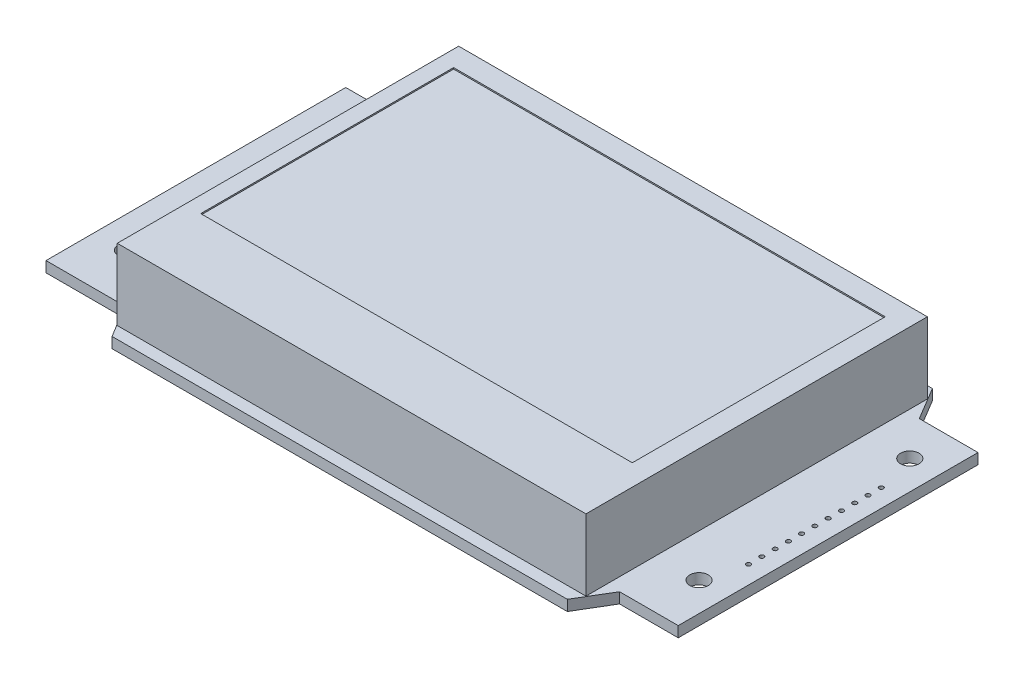
SolidWorks part; units mm, degrees
ref_plane "Front Plane" through (0, 0, 0) normal (0, 0, 1) x (1, 0, 0)
ref_plane "Top Plane" through (0, 0, 0) normal (0, 1, 0) x (1, 0, 0)
ref_plane "Right Plane" through (0, 0, 0) normal (1, 0, 0) x (0, 0, -1)
sketch "Sketch1" plane through (0, 0, 0) normal (0, 1, 0) x (1, 0, 0)
  line L0 (-60.0596, 21.17) -> (-60.0596, -23.9912)
  line L1 (35.1904, 21.17) -> (35.1904, -23.9912)
  line L2 (-45.1752, 26.0849) -> (23.4048, 26.0849)
  line L3 (-45.1752, -28.9151) -> (23.4048, -28.9151)
  line L4 (-60.0596, -1.4106) -> (35.1904, -1.4106) construction
  line L5 (-60.0596, -23.9912) -> (-48.2232, -23.9912)
  line L6 (-60.0596, 21.17) -> (-48.2232, 21.17)
  line L7 (35.1904, 21.17) -> (26.3512, 21.17)
  line L8 (35.1904, -23.9912) -> (26.3512, -23.9912)
  line L9 (-10.8852, 26.0849) -> (-10.8852, -28.9151) construction
  line L10 (-48.2232, -23.9912) -> (-45.1752, -28.9151)
  line L11 (26.3512, -23.9912) -> (23.4048, -28.9151)
  line L12 (23.4048, 26.0849) -> (26.3512, 21.17)
  line L13 (-45.1752, 26.0849) -> (-48.2232, 21.17)
  dimension "D1" = 45.1612
  dimension "D2" = 55
  dimension "D3" = 27.4955
  dimension "D4" = 11.8364
  dimension "D5" = 8.8392
  dimension "D6" = 11.7856
  dimension "D7" = 95.25
  dimension "D8" = 68.58
extrude "Boss-Extrude1" add sketch "Sketch1" along normal blind 1.6
sketch "Sketch2" plane through (0, 1.6, 0) normal (0, 1, 0) x (1, 0, 0)
  line L0 (35.1904, -23.9912) -> (35.1904, 21.17) construction
  line L1 (26.3512, -23.9912) -> (35.1904, -23.9912) construction
  circle A0 centre (-55.2717, 15.2518) radius 1.397
  circle A1 centre (-55.2717, -16.4982) radius 1.397
  circle A2 centre (30.8343, -16.4982) radius 1.397
  circle A3 centre (30.8343, 15.2518) radius 1.397
  dimension "D1" = 2.794
  dimension "D2" = 31.75
  dimension "D3" = 86.106
  dimension "D4" = 4.3561
  dimension "D5" = 7.493
extrude "Cut-Extrude1" cut sketch "Sketch2" against normal through all
sketch "Sketch3" plane through (0, 1.6, 0) normal (0, 1, 0) x (1, 0, 0)
  line L0 (23.4048, 26.0849) -> (-45.1752, 26.0849) construction
  line L1 (-46.2166, 24.3349) -> (24.3954, 24.3349)
  line L2 (-46.2166, 24.3349) -> (-46.2166, -27.1001)
  line L3 (-46.2166, -27.1001) -> (24.3954, -27.1001)
  line L4 (24.3954, 24.3349) -> (24.3954, -27.1001)
  line L5 (35.1904, -23.9912) -> (35.1904, 21.17) construction
  dimension "D1" = 51.435
  dimension "D2" = 70.612
  dimension "D3" = 1.75
  dimension "D4" = 10.795
extrude "Boss-Extrude2" add sketch "Sketch3" along normal blind 10.7315
sketch "Sketch4" plane through (0, 12.3315, 0) normal (0, 1, 0) x (1, 0, 0)
  line L0 (-46.2166, -27.1001) -> (24.3954, -27.1001) construction
  line L1 (-43.8036, 21.1599) -> (21.2204, 21.1599)
  line L2 (-43.8036, 21.1599) -> (-43.8036, -16.9401)
  line L3 (-43.8036, -16.9401) -> (21.2204, -16.9401)
  line L4 (21.2204, 21.1599) -> (21.2204, -16.9401)
  line L5 (-46.2166, 24.3349) -> (-46.2166, -27.1001) construction
  dimension "D1" = 38.1
  dimension "D2" = 65.024
  dimension "D3" = 10.16
  dimension "D4" = 2.413
extrude "Cut-Extrude2" cut sketch "Sketch4" against normal blind 0.2
sketch "Sketch5" plane through (0, 1.6, 0) normal (0, 1, 0) x (1, 0, 0)
  line L0 (35.1904, -23.9912) -> (35.1904, 21.17) construction
  line L1 (35.1904, 21.17) -> (26.3512, 21.17) construction
  circle A0 centre (32.4904, 9.3) radius 0.3302
  dimension "D1" = 0.6604
  dimension "D2" = 2.7
  dimension "D3" = 11.87
extrude "Cut-Extrude3" cut sketch "Sketch5" against normal through all
pattern_linear "LPattern1" count 11 spacing 2 along (0, 0, 1) of "Cut-Extrude3"
